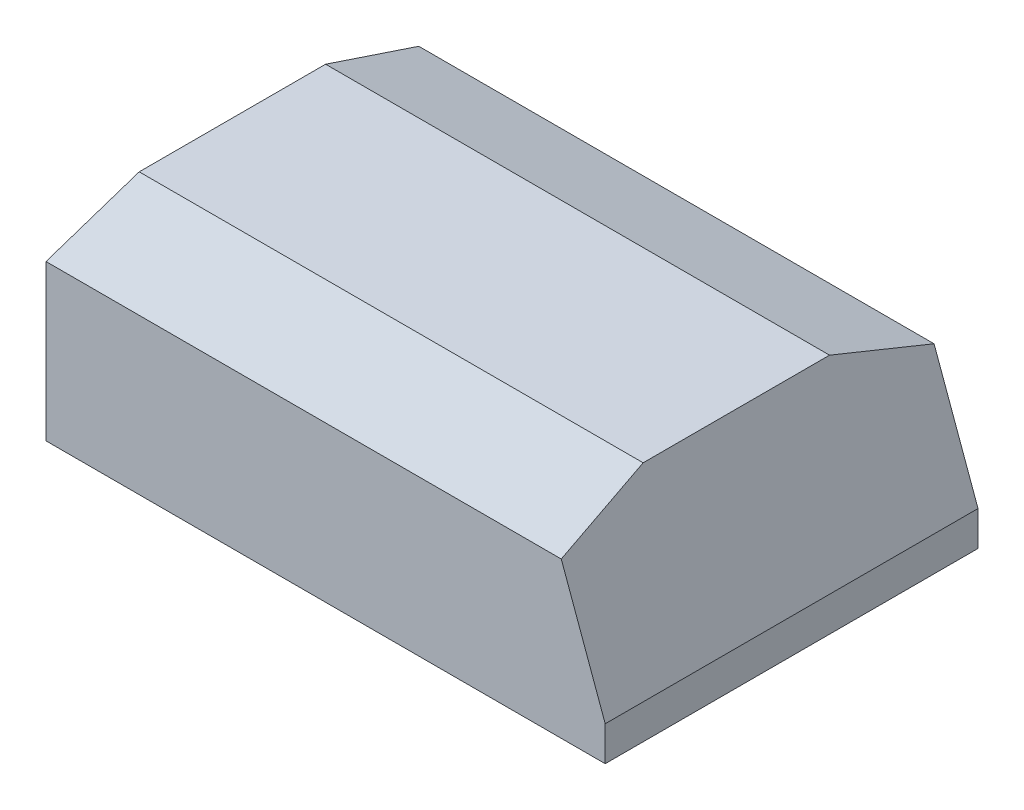
SolidWorks part; units mm, degrees
ref_plane "Front Plane" through (0, 0, 0) normal (0, 0, 1) x (1, 0, 0)
ref_plane "Top Plane" through (0, 0, 0) normal (0, 1, 0) x (1, 0, 0)
ref_plane "Right Plane" through (0, 0, 0) normal (1, 0, 0) x (0, 0, -1)
sketch "Sketch1" plane through (0, 0, 0) normal (0, 1, 0) x (1, 0, 0)
  line L1 (-45, 30) -> (45, 30)
  line L2 (-45, 30) -> (-45, -30)
  line L3 (-45, -30) -> (45, -30)
  line L4 (45, 30) -> (45, -30)
  line L5 (-45, 30) -> (45, -30) construction
  line L6 (-45, -30) -> (45, 30) construction
  point P0 (0, 0)
  dimension "D1" = 90
  dimension "D2" = 60
extrude "Boss-Extrude1" add sketch "Sketch1" along normal blind 30
sketch "Sketch2" plane through (0, 0, 0) normal (0, 0, 1) x (1, 0, 0)
  line L0 (45, 5.568) -> (36.1075, 30)
  line L1 (45, 30) -> (45, 0) construction
  line L2 (-45, 30) -> (45, 30) construction
  line L3 (36.1075, 30) -> (45, 30)
  line L4 (45, 30) -> (45, 5.568)
  point P6 (34.6066, 30)
  dimension "D1" = 26
  dimension "D2" = 20
extrude "Cut-Extrude1" cut sketch "Sketch2" against normal through all both and the other way through all
sketch "Sketch3" plane through (-45, 0, 0) normal (-1, 0, 0) x (0, 0, 1)
  line L0 (15, 30) -> (30, 25)
  line L1 (-30, 30) -> (30, 30) construction
  line L2 (30, 30) -> (30, 0) construction
  line L3 (30, 25) -> (30, 30)
  line L4 (30, 30) -> (15, 30)
  line L5 (-30, 25) -> (-30, 30)
  line L6 (-30, 30) -> (-30, 0) construction
  line L7 (-30, 30) -> (-15, 30)
  line L8 (-15, 30) -> (-30, 25)
  point P11 (-32.5, 20.4571)
  point P13 (-16.1389, 30)
  dimension "D1" = 15
  dimension "D2" = 5
extrude "Cut-Extrude2" cut sketch "Sketch3" against normal through all and the other way through all
equation "\"Length\"= 90"
equation "\"Width\"= 60"
equation "\"D1@Sketch1\"=\"Length\""
equation "\"D2@Sketch1\"=\"Width\""
